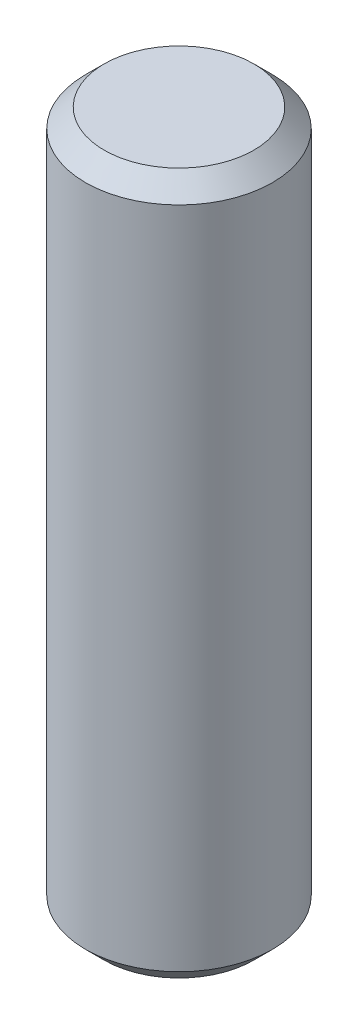
SolidWorks part; units mm, degrees
ref_plane "Front Plane" through (0, 0, 0) normal (0, 0, 1) x (1, 0, 0)
ref_plane "Top Plane" through (0, 0, 0) normal (0, 1, 0) x (1, 0, 0)
ref_plane "Right Plane" through (0, 0, 0) normal (1, 0, 0) x (0, 0, -1)
sketch "Sketch1" plane through (0, 0, 0) normal (0, 0, 1) x (1, 0, 0)
  line L0 (0, 25.8101) -> (0, -60.3218) construction
  line L1 (0, 19.9106) -> (10, 19.9106)
  line L2 (10, 19.9106) -> (10, -55.0894)
  line L3 (10, -55.0894) -> (0, -55.0894)
  line L4 (0, 19.9106) -> (0, -55.0894)
  point P5 (0, -60.3218)
  dimension "D1" = 10
  dimension "D2" = 75
revolve "Revolve1" add sketch "Sketch1" angle 360 about L0
chamfer "Chamfer1" distance 2 angle 45 2 edges at (0, -55.0894, 10) (0, 19.9106, 10)
cosmetic thread "Cosmetic Thread1" parameters "D1"=30, "D2"=17.252
cosmetic thread "Cosmetic Thread2" parameters "D1"=20, "D2"=17.252
